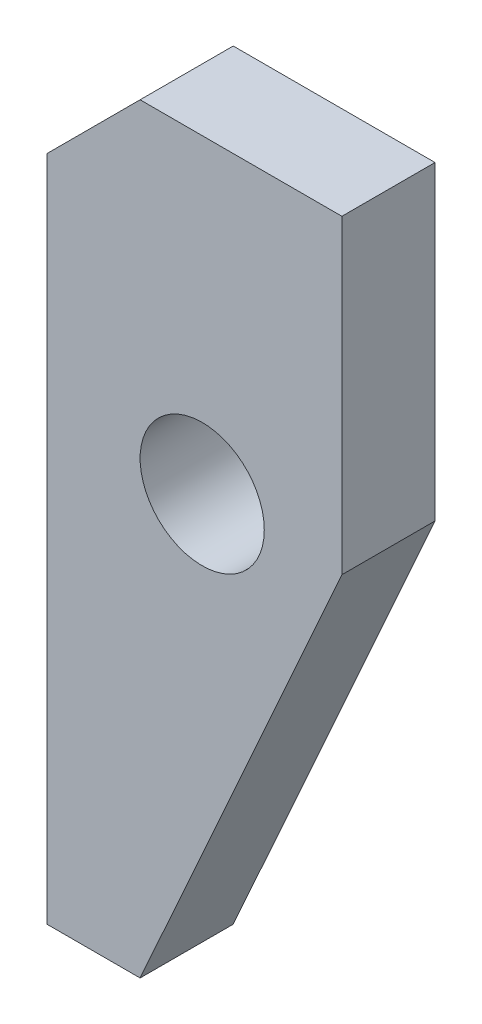
SolidWorks part; units mm, degrees
ref_plane "前视基准面" through (0, 0, 0) normal (0, 0, 1) x (1, 0, 0)
ref_plane "上视基准面" through (0, 0, 0) normal (0, 1, 0) x (1, 0, 0)
ref_plane "右视基准面" through (0, 0, 0) normal (1, 0, 0) x (0, 0, -1)
sketch "草图1" plane through (0, 0, 0) normal (0, 0, 1) x (1, 0, 0)
  line L0 (0, 0) -> (65, 0)
  line L1 (65, 0) -> (65, -100)
  line L2 (65, -100) -> (0, -245)
  line L3 (0, -245) -> (-30, -245)
  line L4 (-30, -245) -> (-30, -30)
  line L5 (-30, -30) -> (0, 0)
  point P3 (0, 0)
  dimension "D1" = 95
  dimension "D2" = 30
  dimension "D3" = 245
  dimension "D4" = 65
  dimension "D5" = 30
  dimension "D6" = 100
extrude "凸台-拉伸1" add sketch "草图1" along normal blind 30
sketch "草图2" plane through (0, 0, 30) normal (0, 0, 1) x (1, 0, 0)
  line L0 (65, -100) -> (65, 0) construction
  line L1 (65, 0) -> (0, 0) construction
  circle A0 centre (20, -100) radius 20
  dimension "D1" = 45
  dimension "D2" = 100
  dimension "D3" = 40
extrude "切除-拉伸1" cut sketch "草图2" against normal through all
